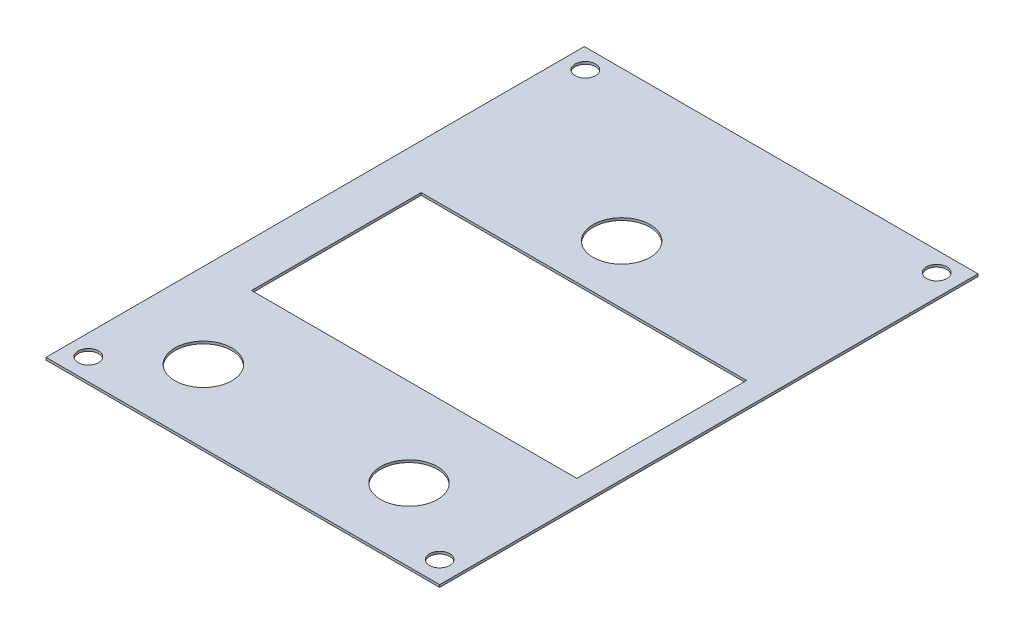
SolidWorks part; units mm, degrees
ref_plane "Front Plane" through (0, 0, 0) normal (0, 0, 1) x (1, 0, 0)
ref_plane "Top Plane" through (0, 0, 0) normal (0, 1, 0) x (1, 0, 0)
ref_plane "Right Plane" through (0, 0, 0) normal (1, 0, 0) x (0, 0, -1)
sketch "Sketch1" plane through (0, 0, 0) normal (0, 1, 0) x (1, 0, 0)
  line L0 (28.246, 0.814) -> (38.046, 0.814) construction
  line L1 (0, 0) -> (43.18, 0) construction
  line L2 (0, 0) -> (0, 61.087) construction
  line L3 (0, 61.087) -> (43.18, 61.087) construction
  line L4 (43.18, 0) -> (43.18, 61.087) construction
  line L5 (2.973, 0.814) -> (12.773, 0.814) construction
  line L6 (2.973, 0.814) -> (2.973, 11.714) construction
  line L7 (2.973, 11.714) -> (12.773, 11.714) construction
  line L8 (12.773, 0.814) -> (12.773, 11.714) construction
  line L9 (28.246, 0.814) -> (28.246, 11.714) construction
  line L10 (28.246, 11.714) -> (38.046, 11.714) construction
  line L11 (38.046, 0.814) -> (38.046, 11.714) construction
  line L12 (7.873, 11.714) -> (7.873, 0.814) construction
  line L13 (15.445, 39.353) -> (25.445, 39.353) construction
  line L14 (15.445, 39.353) -> (15.445, 50.853) construction
  line L15 (15.445, 50.853) -> (25.445, 50.853) construction
  line L16 (25.445, 39.353) -> (25.445, 50.853) construction
  line L17 (33.146, 11.714) -> (33.146, 0.814) construction
  line L18 (20.445, 50.853) -> (20.445, 39.353) construction
  line L20 (-2.54, 63.5) -> (45.847, 63.5)
  line L21 (-2.54, 63.5) -> (-2.54, -2.667)
  line L22 (-2.54, -2.667) -> (45.847, -2.667)
  line L23 (45.847, 63.5) -> (45.847, -2.667)
  line L24 (2.973, 37.9333) -> (42.973, 37.9333)
  line L25 (2.973, 37.9333) -> (2.973, 17.0736)
  line L26 (2.973, 17.0736) -> (42.973, 17.0736)
  line L27 (42.973, 37.9333) -> (42.973, 17.0736)
  circle A0 centre (0, 61.087) radius 1.25
  circle A1 centre (43.18, 61.087) radius 1.25
  circle A2 centre (43.18, 0) radius 1.25
  circle A3 centre (0, 0) radius 1.25
  circle A4 centre (20.445, 45.103) radius 3.5
  circle A5 centre (33.146, 6.264) radius 3.5
  circle A7 centre (7.873, 6.264) radius 3.5
  dimension "D3" = 2.5
  dimension "D4" = 2.5
  dimension "D5" = 2.5
  dimension "D6" = 2.5
  dimension "D18" = 7
  dimension "D19" = 7
  dimension "D20" = 7
  dimension "D21" = 2.54
  dimension "D22" = 2.413
  dimension "D23" = 2.667
  dimension "D24" = 2.667
  dimension "D25" = 40
  dimension "D1" = 61.087
  dimension "D2" = 43.18
  dimension "D7" = 9.8
  dimension "D8" = 10.9
  dimension "D9" = 10.9
  dimension "D10" = 9.8
  dimension "D11" = 15.473
  dimension "D12" = 2.973
  dimension "D13" = 0.814
  dimension "D14" = 10
  dimension "D15" = 11.5
  dimension "D16" = 2.672
  dimension "D17" = 10.234
  dimension "D26" = 20.8597
  dimension "D27" = 5.513
  dimension "D28" = 19.7406
extrude "Boss-Extrude1" add sketch "Sketch1" along normal blind 0.3
